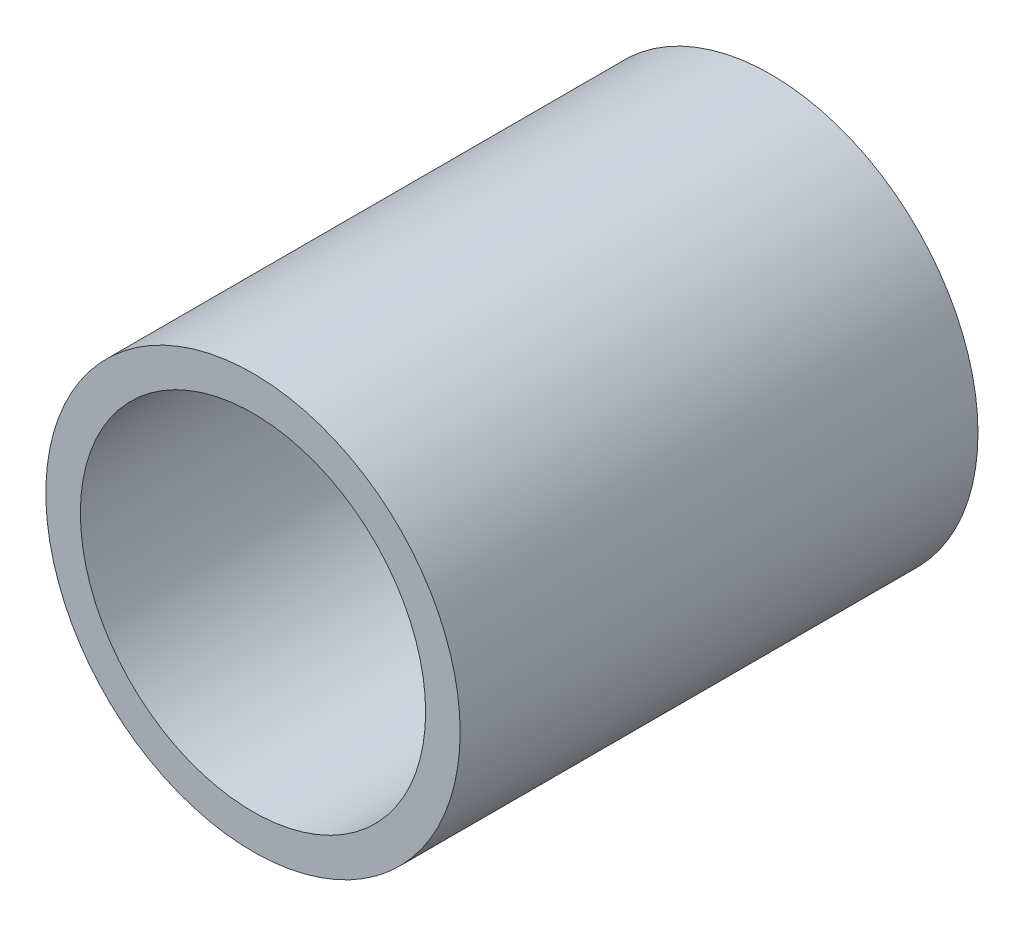
SolidWorks part; units mm, degrees
ref_plane "前视基准面" through (0, 0, 0) normal (0, 0, 1) x (1, 0, 0)
ref_plane "上视基准面" through (0, 0, 0) normal (0, 1, 0) x (1, 0, 0)
ref_plane "右视基准面" through (0, 0, 0) normal (1, 0, 0) x (0, 0, -1)
sketch "草图1" plane through (0, 0, 0) normal (0, 0, 1) x (1, 0, 0)
  circle A0 centre (0, 0) radius 5
  circle A1 centre (0, 0) radius 6
  dimension "D1" = 12
  dimension "D2" = 10
extrude "凸台-拉伸1" add sketch "草图1" along normal blind 15
